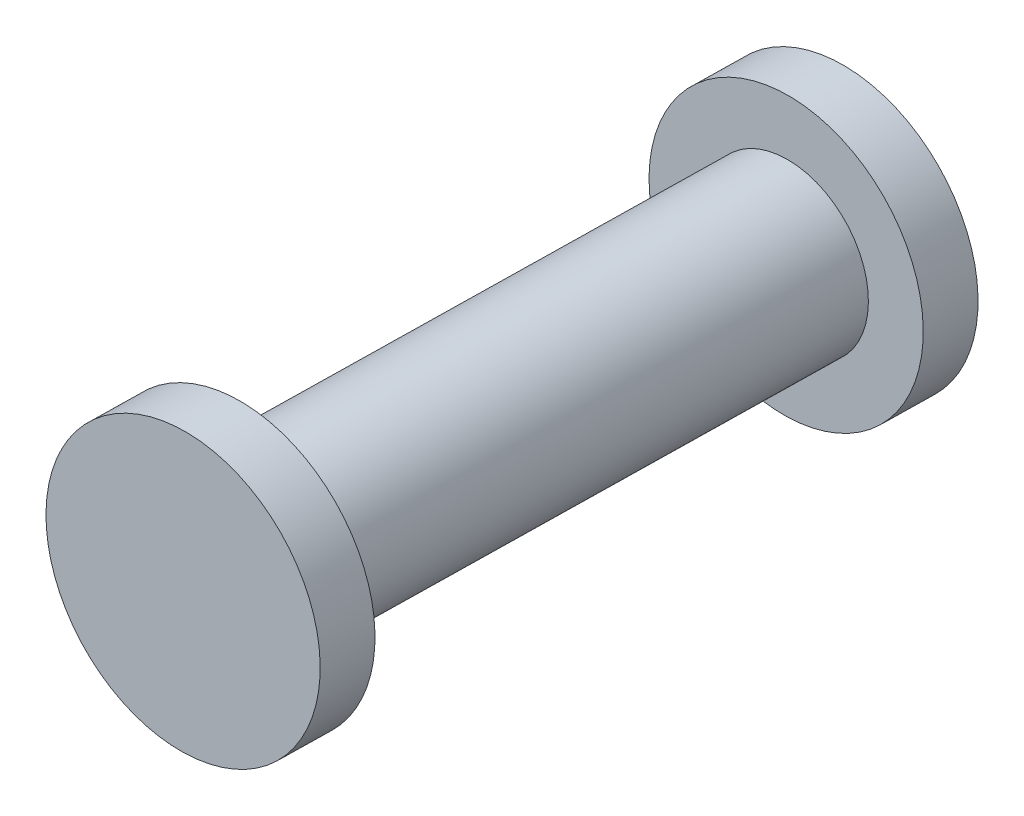
SolidWorks part; units mm, degrees
material "Alumina"
ref_plane "Front Plane" through (0, 0, 0) normal (0, 0, 1) x (1, 0, 0)
ref_plane "Top Plane" through (0, 0, 0) normal (0, 1, 0) x (1, 0, 0)
ref_plane "Right Plane" through (0, 0, 0) normal (1, 0, 0) x (0, 0, -1)
sketch "Sketch1" plane through (0, 0, 0) normal (0, 0, 1) x (1, 0, 0)
  line L0 (0, 0) -> (0, 12)
  line L3 (-1.5, 1) -> (-2.5, 1)
  line L4 (-2.5, 1) -> (-2.5, 0)
  line L5 (-2.5, 0) -> (0, 0)
  line L6 (0, 12) -> (-2.5, 12)
  line L7 (-2.5, 12) -> (-2.5, 11)
  line L8 (-2.5, 11) -> (-1.5, 11)
  line L9 (-1.5, 11) -> (-1.5, 1)
  dimension "D1" = 12
  dimension "D2" = 1
  dimension "D3" = 2.5
  dimension "D4" = 1.5
revolve "Revolve1" add sketch "Sketch1" angle 360 about L0
move or copy body "Body-Move/Copy1" bodies to move or copy 101 copy no rotation origin (-2.3466, 4.6121, -2.3466) rotation axis (0.574, 0.5841, 0.574) rotation angle 119.424
